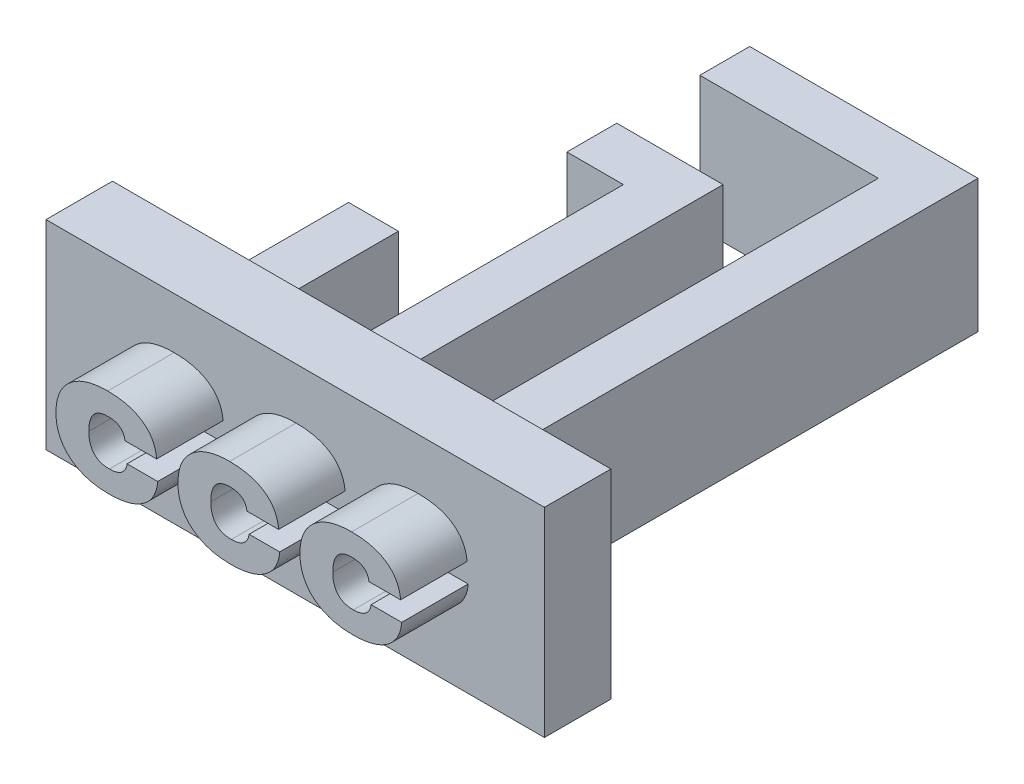
SolidWorks part; units mm, degrees
ref_plane "Front Plane" through (0, 0, 0) normal (0, 0, 1) x (1, 0, 0)
ref_plane "Top Plane" through (0, 0, 0) normal (0, 1, 0) x (1, 0, 0)
ref_plane "Right Plane" through (0, 0, 0) normal (1, 0, 0) x (0, 0, -1)
sketch "Sketch1" plane through (0, 0, 0) normal (0, 0, 1) x (1, 0, 0)
  line L1 (-7.5, 3) -> (7.5, 3)
  line L2 (-7.5, 3) -> (-7.5, -3)
  line L3 (-7.5, -3) -> (7.5, -3)
  line L4 (7.5, 3) -> (7.5, -3)
  line L5 (-7.5, 3) -> (7.5, -3) construction
  line L6 (-7.5, -3) -> (7.5, 3) construction
  point P0 (0, 0)
  dimension "D1" = 15
  dimension "D2" = 6
extrude "Boss-Extrude1" add sketch "Sketch1" along normal blind 2
sketch "Sketch2" plane through (0, 0, 2) normal (0, 0, 1) x (1, 0, 0)
  text T0 "CCC" font "Swis721 Blk BT" height in points 10
extrude "Boss-Extrude2" add sketch "Sketch2" along normal blind 2
sketch "Sketch3" plane through (0, 0, 0) normal (0, 1, 0) x (1, 0, 0)
  line L0 (7.5, 0) -> (-7.5, 0) construction
  line L1 (2.9487, 0) -> (4.4487, 0)
  line L2 (2.9487, 0) -> (2.9487, 12.6)
  line L3 (-3.644, -2) -> (-3.644, 5.3789) construction
  line L4 (4.4487, 0) -> (4.4487, 14.1)
  line L5 (-4.394, 0) -> (-2.894, 0)
  line L6 (-4.394, 0) -> (-4.394, 4)
  line L7 (0.0274, -2) -> (0.0274, 4.6797) construction
  line L8 (-2.894, 0) -> (-2.894, 4)
  line L9 (-2.894, 4) -> (-4.394, 4)
  line L10 (-0.7226, 0) -> (0.7774, 0)
  line L13 (-0.7226, 0) -> (-0.7226, 8.6)
  line L14 (3.6987, -2) -> (3.6987, 2.787) construction
  line L15 (0.7774, 0) -> (0.7774, 10.1)
  line L16 (0.7774, 10.1) -> (-2.4226, 10.1)
  line L17 (-2.4226, 14.1) -> (4.4487, 14.1)
  line L18 (-0.7226, 8.6) -> (-2.4226, 8.6)
  line L19 (-2.4226, 10.1) -> (-2.4226, 8.6)
  line L20 (-2.4226, 14.1) -> (-2.4226, 12.6)
  line L21 (-2.4226, 12.6) -> (2.9487, 12.6)
  dimension "D1" = 1.5
  dimension "D2" = 4
  dimension "D3" = 1.5
  dimension "D4" = 1.5
  dimension "D5" = 4.6
  dimension "D6" = 1.5
  dimension "D7" = 2.5
  dimension "D8" = 1.5
  dimension "D9" = 1.7
extrude "Boss-Extrude3" add sketch "Sketch3" along normal mid plane 4
